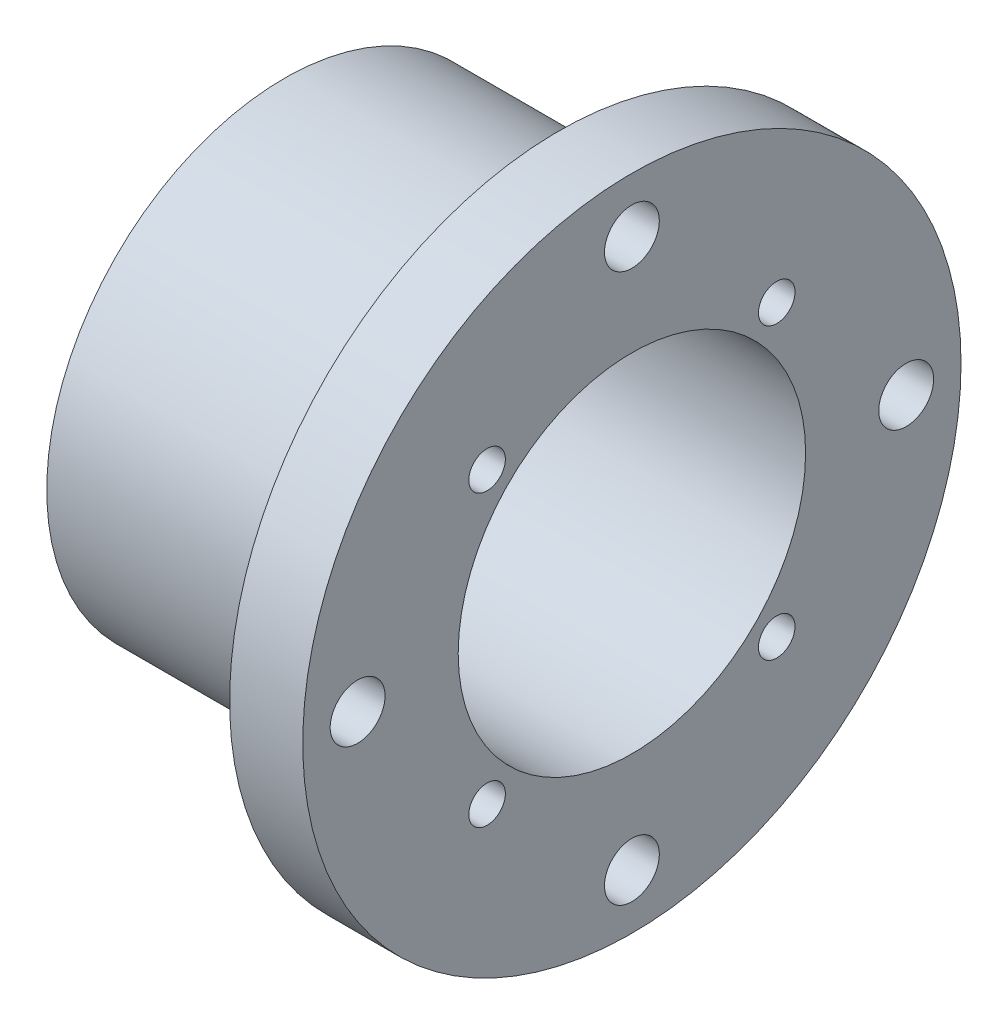
SolidWorks part; units mm, degrees
ref_plane "Front Plane" through (0, 0, 0) normal (0, 0, 1) x (1, 0, 0)
ref_plane "Top Plane" through (0, 0, 0) normal (0, 1, 0) x (1, 0, 0)
ref_plane "Right Plane" through (0, 0, 0) normal (1, 0, 0) x (0, 0, -1)
sketch "Sketch1" plane through (0, 0, 0) normal (1, 0, 0) x (0, 0, -1)
  circle A0 centre (0, 0) radius 13
  circle A1 centre (0, 0) radius 9.5
  dimension "D1" = 26
  dimension "D2" = 19
extrude "Boss-Extrude1" add sketch "Sketch1" along normal blind 15
sketch "Sketch2" plane through (15, 0, 0) normal (1, 0, 0) x (0, 0, -1)
  circle A0 centre (0, 0) radius 9.5 construction
  circle A1 centre (0, 0) radius 9.5
  circle A2 centre (0, 0) radius 18
  dimension "D1" = 36
extrude "Boss-Extrude2" add sketch "Sketch2" along normal blind 4
sketch "Sketch3" plane through (0, 0, 0) normal (-1, 0, 0) x (0, 0, 1)
  circle A0 centre (0, 0) radius 8.5
  circle A1 centre (0, 0) radius 9.5 construction
  circle A2 centre (0, 0) radius 9.5
  dimension "D1" = 17
extrude "Boss-Extrude3" add sketch "Sketch3" against normal blind 2
sketch "Sketch4" plane through (19, 0, 0) normal (1, 0, 0) x (0, 0, -1)
  circle A0 centre (0, 0) radius 15 construction
  circle A1 centre (0, 15) radius 1.5
  circle A2 centre (15, 0) radius 1.5
  circle A3 centre (0, -15) radius 1.5
  circle A4 centre (-15, 0) radius 1.5
  point P14 (0, 0)
  dimension "D1" = 30
  dimension "D2" = 3
  dimension "D4" = 15
  dimension "D5" = 15
  dimension "D3" = 4
extrude "Cut-Extrude1" cut sketch "Sketch4" against normal through all
sketch "Sketch5" plane through (19, 0, 0) normal (1, 0, 0) x (0, 0, -1)
  line L0 (0, 0) -> (0, 11.2) construction
  line L1 (0, 0) -> (7.9196, 7.9196) construction
  circle A0 centre (0, 0) radius 13 construction
  circle A1 centre (0, 0) radius 13 construction
  circle A2 centre (0, 0) radius 11.2 construction
  circle A3 centre (7.9196, 7.9196) radius 1
  circle A4 centre (7.9196, -7.9196) radius 1
  circle A5 centre (-7.9196, -7.9196) radius 1
  circle A6 centre (-7.9196, 7.9196) radius 1
  point P15 (0, 0)
  dimension "D1" = 22.4
  dimension "D2" = 2
  dimension "D3" = 4
  dimension "D4" = 45
extrude "Cut-Extrude2" cut sketch "Sketch5" against normal blind 8
equation "\"shaft-diameter\" =20mm"
equation "\"key-length\"=12mm"
equation "\"key-width\"=4mm"
equation "\"flippershaft-wormgear-diameter\" = 35mm"
equation "\"shaft-ring-groove-depth\"=0.5mm"
equation "\"shaft-ring-groove-width\" = 1.3mm"
equation "\"mini-shaft-diameter\" = 12mm"
equation "\"mini-flipper-shaft-diameter\"= 26mm"
equation "\"D1@Sketch1\"=\"mini-flipper-shaft-diameter\""
equation "\"D5@Sketch4\"=\"D1@Sketch4\"/2"
equation "\"D4@Sketch4\"=\"D1@Sketch4\"/2"
